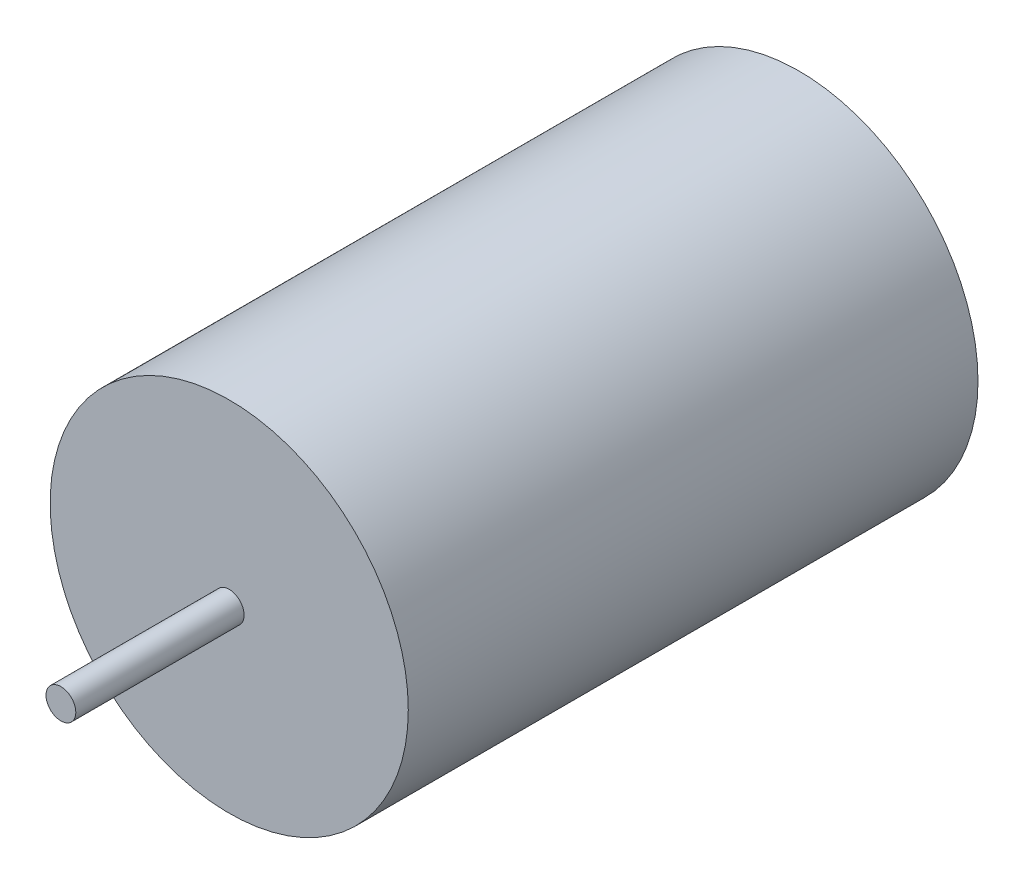
SolidWorks part; units mm, degrees
ref_plane "Front Plane" through (0, 0, 0) normal (0, 0, 1) x (1, 0, 0)
ref_plane "Top Plane" through (0, 0, 0) normal (0, 1, 0) x (1, 0, 0)
ref_plane "Right Plane" through (0, 0, 0) normal (1, 0, 0) x (0, 0, -1)
sketch "Sketch1" plane through (0, 0, 0) normal (0, 0, 1) x (1, 0, 0)
  circle A0 centre (0, 0) radius 13.83
  dimension "D1" = 27.66
extrude "Boss-Extrude1" add sketch "Sketch1" along normal blind 44
sketch "Sketch2" plane through (0, 0, 44) normal (0, 0, 1) x (1, 0, 0)
  circle A0 centre (0, 0) radius 1.15
  dimension "D1" = 2.3
extrude "Boss-Extrude2" add sketch "Sketch2" along normal blind 13
